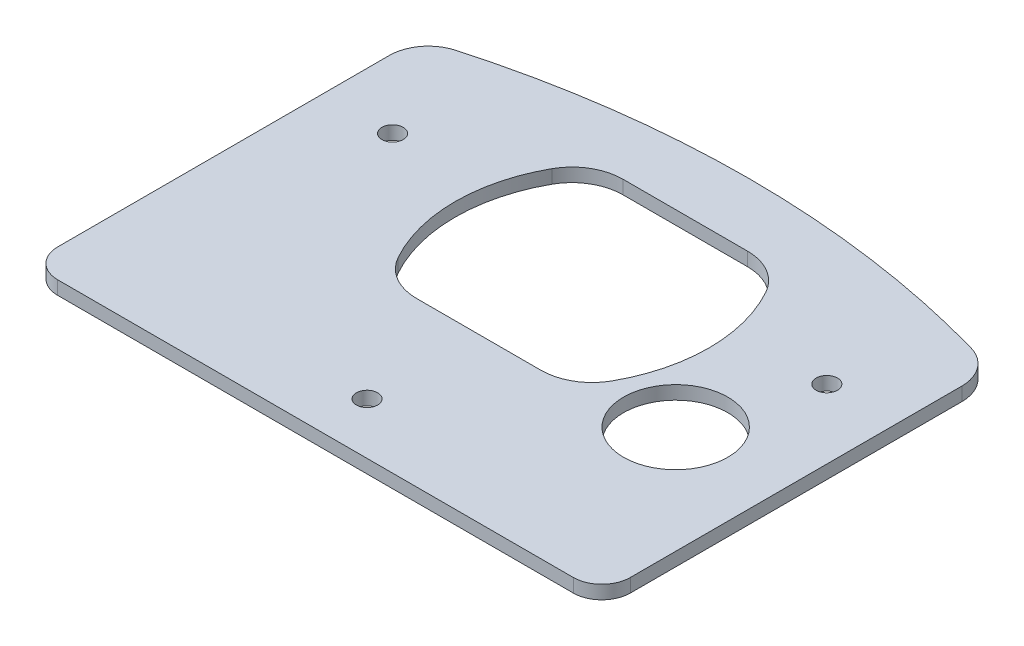
SolidWorks part; units mm, degrees
ref_plane "Front Plane" through (0, 0, 0) normal (0, 0, 1) x (1, 0, 0)
ref_plane "Top Plane" through (0, 0, 0) normal (0, 1, 0) x (1, 0, 0)
ref_plane "Right Plane" through (0, 0, 0) normal (1, 0, 0) x (0, 0, -1)
sketch "Sketch1" plane through (0, 0, 0) normal (0, 1, 0) x (1, 0, 0)
  line L0 (-67.25, 0) -> (67.25, 0)
  line L1 (67.25, 0) -> (67.25, 91.4083)
  line L2 (-67.25, 0) -> (-67.25, 91.4083)
  line L3 (0, 0) -> (0, 69.1) construction
  line L4 (-51, 69.1) -> (51, 69.1) construction
  line L5 (-14.6222, 40.35) -> (14.6222, 40.35) construction
  line L6 (-14.6222, 84.85) -> (14.6222, 84.85) construction
  line L7 (-14.6222, 86.85) -> (14.6222, 86.85)
  line L8 (-14.6222, 38.35) -> (14.6222, 38.35)
  arc A1 (-67.25, 91.4083) -> (67.25, 91.4083) centre (0, -121) cw
  circle A2 centre (-51, 69.1) radius 2.5
  circle A3 centre (51, 69.1) radius 2.5
  circle A4 centre (0, 12.1) radius 2.5
  circle A5 centre (42, 42.6) radius 12.25
  arc A6 (-23.3612, 45.4889) -> (-23.3612, 79.7111) centre (7.4, 62.6) cw construction
  arc A7 (23.3612, 79.7111) -> (23.3612, 45.4889) centre (-7.4, 62.6) cw construction
  arc A8 (-14.6222, 40.35) -> (-23.3612, 45.4889) centre (-14.6222, 50.35) cw construction
  arc A9 (14.6222, 40.35) -> (23.3612, 45.4889) centre (14.6222, 50.35) ccw construction
  arc A10 (14.6222, 84.85) -> (23.3612, 79.7111) centre (14.6222, 74.85) cw construction
  arc A11 (-23.3612, 79.7111) -> (-14.6222, 84.85) centre (-14.6222, 74.85) cw construction
  arc A12 (-25.109, 80.6833) -> (-14.6222, 86.85) centre (-14.6222, 74.85) cw
  arc A13 (14.6222, 86.85) -> (25.109, 80.6833) centre (14.6222, 74.85) cw
  arc A14 (25.109, 80.6833) -> (25.109, 44.5167) centre (-7.4, 62.6) cw
  arc A15 (14.6222, 38.35) -> (25.109, 44.5167) centre (14.6222, 50.35) ccw
  arc A16 (-14.6222, 38.35) -> (-25.109, 44.5167) centre (-14.6222, 50.35) cw
  arc A17 (-25.109, 44.5167) -> (-25.109, 80.6833) centre (7.4, 62.6) cw
  point P2 (0, 0)
  point P8 (0, 101.8)
  point P18 (0, 69.1)
  point P25 (0, 40.35)
  point P26 (11.305, 84.85)
  point P29 (-27.8, 62.6)
  point P30 (27.8, 62.6)
  point P31 (-19.876, 40.35)
  point P34 (19.876, 40.35)
  point P37 (19.876, 84.85)
  point P40 (-19.876, 84.85)
  dimension "D2" = 222.8
  dimension "D4" = 12.1
  dimension "D5" = 5
  dimension "D8" = 24.5
  dimension "D11" = 55.6
  dimension "D14" = 35.2
  dimension "D15" = 10
  dimension "D1" = 134.5
  dimension "D3" = 101.8
  dimension "D6" = 57
  dimension "D7" = 102
  dimension "D9" = 42.6
  dimension "D10" = 25.25
  dimension "D12" = 44.5
  dimension "D13" = 40.35
  dimension "D16" = 2
extrude "Boss-Extrude1" add sketch "Sketch1" along normal blind 3.175
fillet "Fillet1" radius 9.2 2 edges at (-67.25, 1.5875, -91.4083) (67.25, 1.5875, -91.4083)
fillet "Fillet2" radius 6.7 2 edges at (67.25, 1.5875, 0) (-67.25, 1.5875, 0)
